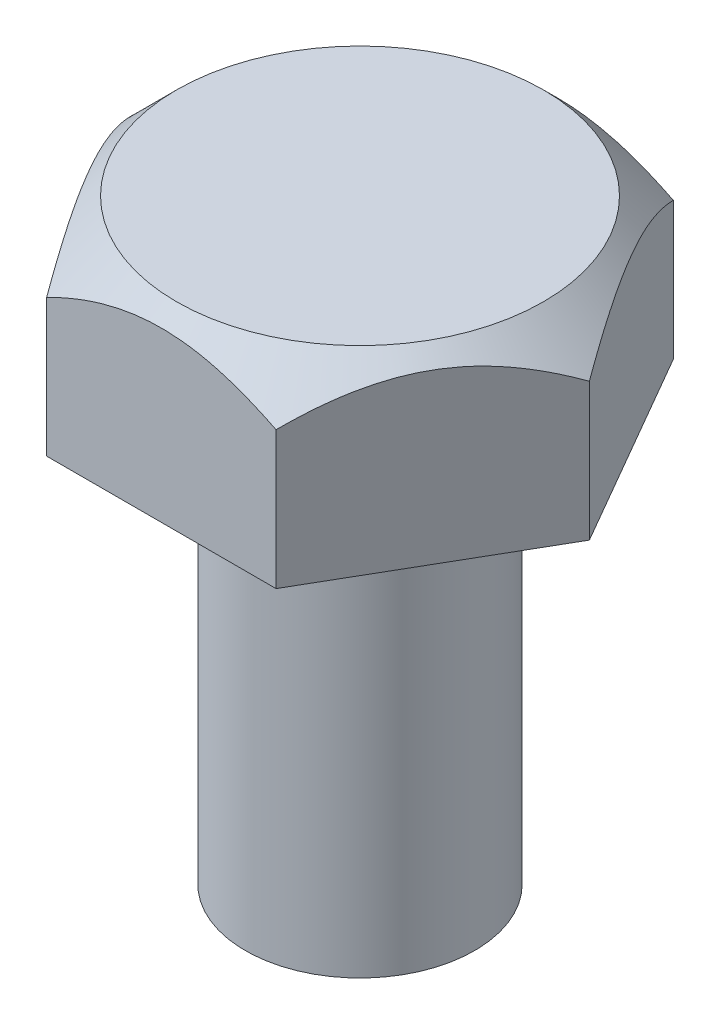
SolidWorks part; units mm, degrees
ref_plane "Front Plane" through (0, 0, 0) normal (0, 0, 1) x (1, 0, 0)
ref_plane "Top Plane" through (0, 0, 0) normal (0, 1, 0) x (1, 0, 0)
ref_plane "Right Plane" through (0, 0, 0) normal (1, 0, 0) x (0, 0, -1)
sketch "Sketch1" plane through (0, 0, 0) normal (0, 1, 0) x (1, 0, 0)
  circle A0 centre (0, 0) radius 2.5
  dimension "D1" = 5
extrude "Boss-Extrude1" add sketch "Sketch1" along normal blind 13
sketch "Sketch2" plane through (0, 13, 0) normal (0, 1, 0) x (1, 0, 0)
  line L1 (5, 0) -> (2.5, 4.3301)
  line L2 (2.5, 4.3301) -> (-2.5, 4.3301)
  line L3 (-2.5, 4.3301) -> (-5, 0)
  line L4 (-5, 0) -> (-2.5, -4.3301)
  line L5 (-2.5, -4.3301) -> (2.5, -4.3301)
  line L6 (2.5, -4.3301) -> (5, 0)
  circle A0 centre (0, 0) radius 4.3301 construction
  dimension "D1" = 10
extrude "Boss-Extrude2" add sketch "Sketch2" against normal blind 4
sketch "Sketch3" plane through (0, 0, 0) normal (0, 0, 1) x (1, 0, 0)
  line L0 (4, 13) -> (5, 12)
  line L1 (2.5, 13) -> (5, 13) construction
  line L2 (5, 9) -> (5, 13) construction
  line L3 (5, 12) -> (5, 13)
  line L4 (5, 13) -> (4, 13)
  line L5 (0, 0) -> (0, 13.2417) construction
  dimension "D1" = 1
  dimension "D2" = 1
revolve "Cut-Revolve1" cut sketch "Sketch3" angle 360 about L5
